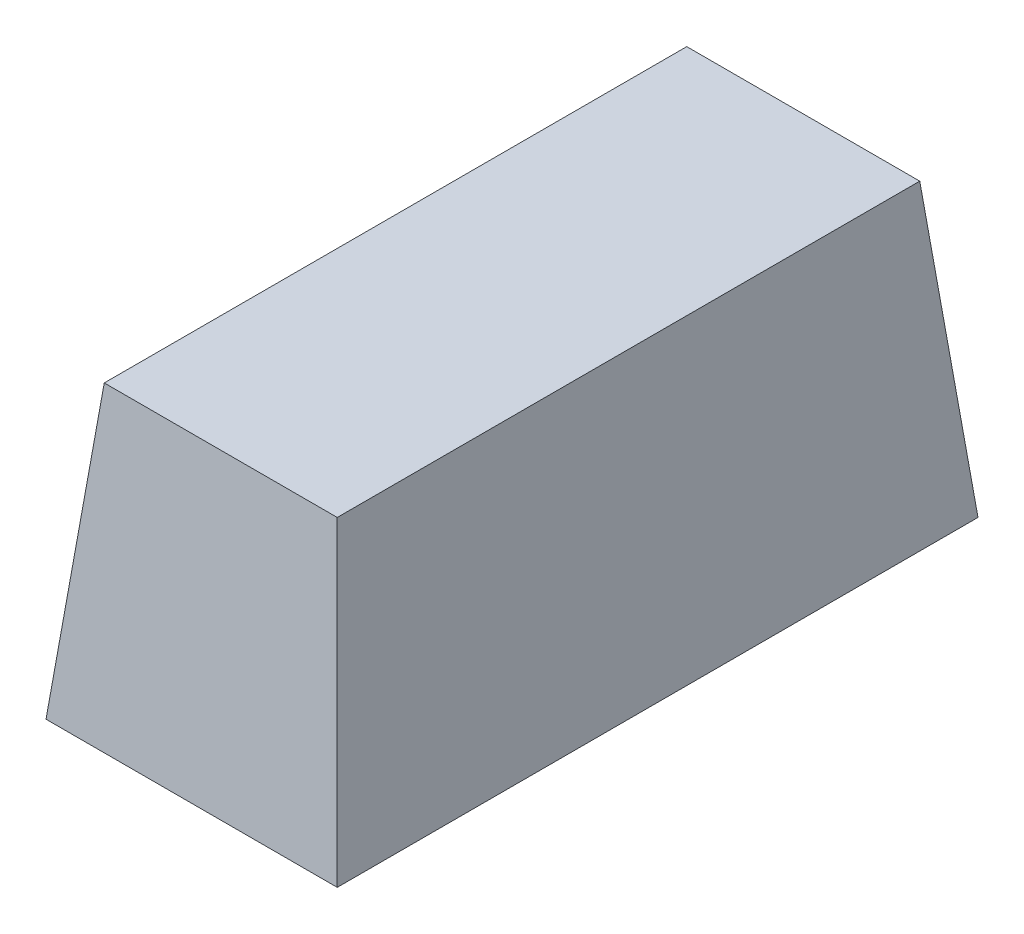
SolidWorks part; units mm, degrees
ref_plane "Front Plane" through (0, 0, 0) normal (0, 0, 1) x (1, 0, 0)
ref_plane "Top Plane" through (0, 0, 0) normal (0, 1, 0) x (1, 0, 0)
ref_plane "Right Plane" through (0, 0, 0) normal (1, 0, 0) x (0, 0, -1)
sketch "Sketch1" plane through (0, 0, 0) normal (0, 1, 0) x (1, 0, 0)
  line L1 (0, 0) -> (20, 0)
  line L2 (0, 0) -> (0, 44)
  line L3 (0, 44) -> (20, 44)
  line L4 (20, 0) -> (20, 44)
ref_plane "Plane1" through (0, 0, 0) normal (0, 1, 0) x (1, 0, 0)
ref_plane "Plane2" through (0, 20, 0) normal (0, 1, 0) x (1, 0, 0)
sketch "Sketch3" plane through (0, 20, 0) normal (0, 1, 0) x (1, 0, 0)
  line L0 (2, 42) -> (2, 2)
  line L1 (2, 2) -> (18, 2)
  line L2 (0, 44) -> (20, 44) construction
  line L3 (2, 42) -> (18, 42)
  line L4 (0, 0) -> (0, 44) construction
  line L5 (18, 42) -> (18, 2)
  dimension "D1" = 2
  dimension "D2" = 40
  dimension "D3" = 2
  dimension "D4" = 16
  dimension "D5" = 0
loft "Loft1" add profiles "Sketch1" section "Sketch1" section "Sketch3"
